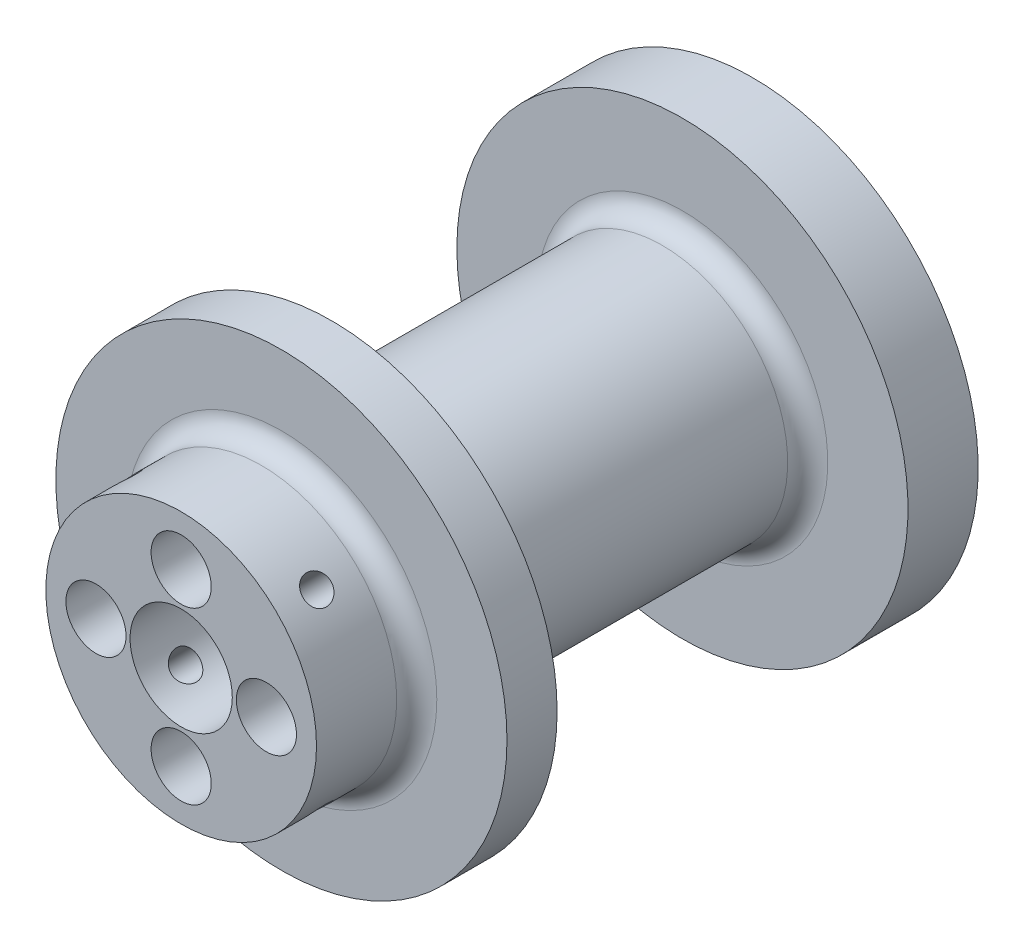
SolidWorks part; units mm, degrees
ref_plane "Спереди" through (0, 0, 0) normal (0, 0, 1) x (1, 0, 0)
ref_plane "Сверху" through (0, 0, 0) normal (0, 1, 0) x (1, 0, 0)
ref_plane "Справа" through (0, 0, 0) normal (1, 0, 0) x (0, 0, -1)
other "Configuration Table"
sketch "Эскиз1" plane through (0, 0, 0) normal (0, 0, 1) x (1, 0, 0)
  circle A0 centre (0, 0) radius 5.1
  circle A1 centre (0, 0) radius 12.5
  dimension "D1" = 10.2
  dimension "D2" = 25
extrude "Бобышка-Вытянуть1" add sketch "Эскиз1" along normal blind 35
sketch "Эскиз2" plane through (0, 0, 0) normal (0, 0, -1) x (-1, 0, 0)
  circle A0 centre (0, 0) radius 5.1
  circle A1 centre (0, 0) radius 22.5
  circle A2 centre (0, 0) radius 5.1 construction
  dimension "D1" = 45
extrude "Бобышка-Вытянуть2" add sketch "Эскиз2" along normal blind 7
sketch "Эскиз3" plane through (0, 0, 35) normal (0, 0, 1) x (1, 0, 0)
  line L0 (-8.5, 0) -> (8.5, 0) construction
  line L1 (0, -8.5) -> (0, 8.5) construction
  circle A0 centre (0, 8.5) radius 1.4
  circle A1 centre (8.5, 0) radius 1.4
  circle A2 centre (0, -8.5) radius 1.4
  circle A3 centre (-8.5, 0) radius 1.4
  point P4 (0, 0)
  point P8 (0, 0)
  dimension "D2" = 2.8
  dimension "D1" = 17
extrude "Вырез-Вытянуть1" cut sketch "Эскиз3" against normal blind 20
fillet "Скругление1" radius 2 1 edges at (12.5, 0, 0)
sketch "Эскиз4" plane through (0, 0, 35) normal (0, 0, 1) x (1, 0, 0)
  circle A0 centre (0, 0) radius 5.1
  circle A1 centre (0, 8.5) radius 1.55
  circle A2 centre (8.5, 0) radius 1.55
  circle A3 centre (0, -8.5) radius 1.55
  circle A4 centre (-8.5, 0) radius 1.55
  circle A5 centre (0, 0) radius 22.5
  circle A6 centre (0, 0) radius 5.1 construction
  circle A7 centre (0, 0) radius 22.5 construction
  dimension "D1" = 3.1
extrude "Бобышка-Вытянуть3" add sketch "Эскиз4" along normal blind 5 separate body
sketch "Эскиз5" plane through (0, 0, 40) normal (0, 0, 1) x (1, 0, 0)
  circle A0 centre (0, 0) radius 5.1
  circle A1 centre (0, 0) radius 13.5
  circle A2 centre (0, 8.5) radius 3
  circle A3 centre (8.5, 0) radius 3
  circle A4 centre (0, -8.5) radius 3
  circle A5 centre (-8.5, 0) radius 3
  circle A6 centre (-8.5, 0) radius 1.55 construction
  circle A7 centre (0, 0) radius 5.1 construction
  dimension "D1" = 6
  dimension "D2" = 27
extrude "Бобышка-Вытянуть4" add sketch "Эскиз5" along normal blind 10
fillet "Скругление2" radius 2 1 edges at (13.5, 0, 40)
ref_plane "Плоскость1" through (9.5459, 9.5459, 0) normal (0.7071, 0.7071, 0) x (0, 0, -1)
sketch "Эскиз6" plane through (9.5459, 9.5459, 0) normal (0.7071, 0.7071, 0) x (0, 0, -1)
  line L0 (-50, 0) -> (-42, 0) construction
  line L1 (-50, 5.1) -> (-50, -5.1) construction
  line L2 (-42, 13.5) -> (-42, -13.5) construction
  line L3 (-50, 13.5) -> (-50, -13.5) construction
  circle A0 centre (-46, 0) radius 1.4
  dimension "D1" = 2.8
  dimension "D2" = 4
extrude "Вырез-Вытянуть2" cut sketch "Эскиз6" against normal through all
pattern_circular "Круговой массив1" count 2 every 90 about axis through (0, 0, 40) along (0, 0, -1) of "Вырез-Вытянуть2"
